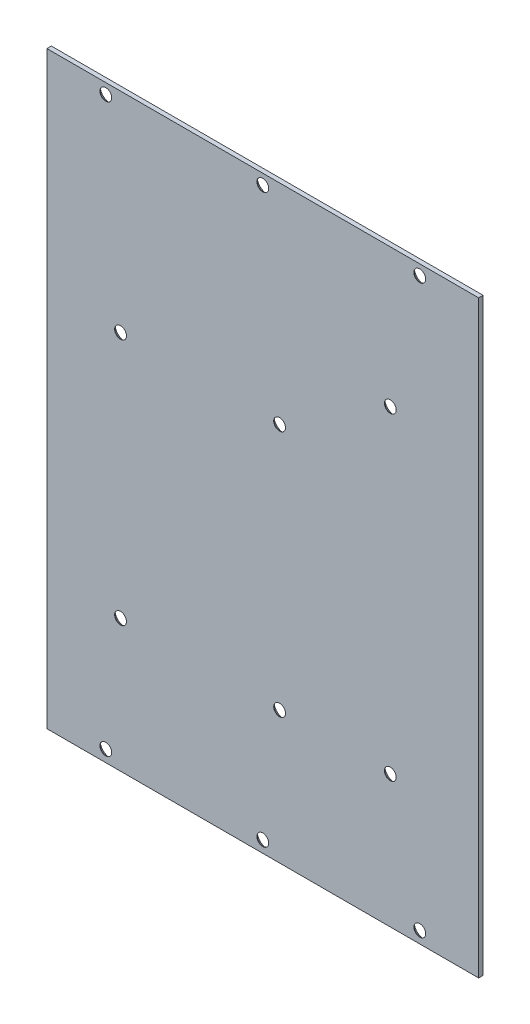
SolidWorks part; units mm, degrees
ref_plane "Спереди" through (0, 0, 0) normal (0, 0, 1) x (1, 0, 0)
ref_plane "Сверху" through (0, 0, 0) normal (0, 1, 0) x (1, 0, 0)
ref_plane "Справа" through (0, 0, 0) normal (1, 0, 0) x (0, 0, -1)
sketch "Эскиз1" plane through (0, 0, 0) normal (0, 0, 1) x (1, 0, 0)
  line L1 (0, 0) -> (146.6, 0)
  line L2 (0, 0) -> (0, 200)
  line L3 (0, 200) -> (146.6, 200)
  line L4 (146.6, 0) -> (146.6, 200)
  dimension "D1" = 146.6
  dimension "D2" = 200
extrude "Бобышка-Вытянуть1" add sketch "Эскиз1" along normal blind 1.5
sketch "Эскиз2" plane through (0, 0, 1.5) normal (0, 0, 1) x (1, 0, 0)
  line L0 (0, 0) -> (146.6, 0) construction
  line L1 (0, 200) -> (0, 0) construction
  line L2 (146.6, 200) -> (0, 200) construction
  circle A0 centre (20, 4) radius 2
  circle A1 centre (20, 196.5) radius 2
  circle A2 centre (73.3, 196.5) radius 2
  circle A3 centre (73.3, 4) radius 2
  circle A4 centre (126.6, 196.5) radius 2
  circle A5 centre (126.6, 4) radius 2
  dimension "D1" = 4
  dimension "D2" = 4
  dimension "D3" = 20
  dimension "D4" = 3.5
  dimension "D5" = 3
extrude "Вырез-Вытянуть1" cut sketch "Эскиз2" against normal through all
sketch "Эскиз3" plane through (0, 0, 1.5) normal (0, 0, 1) x (1, 0, 0)
  line L0 (0, 0) -> (146.6, 0) construction
  line L1 (0, 200) -> (0, 0) construction
  circle A0 centre (25, 45) radius 2
  circle A1 centre (79, 45) radius 2
  circle A2 centre (79, 129) radius 2
  circle A3 centre (25, 129) radius 2
  dimension "D1" = 4
  dimension "D2" = 45
  dimension "D3" = 25
extrude "Вырез-Вытянуть2" cut sketch "Эскиз3" against normal through all
sketch "Эскиз4" plane through (0, 0, 1.5) normal (0, 0, 1) x (1, 0, 0)
  line L0 (146.6, 0) -> (146.6, 200) construction
  line L1 (0, 0) -> (146.6, 0) construction
  circle A0 centre (116.6, 45) radius 2
  circle A1 centre (116.6, 153) radius 2
  dimension "D1" = 4
  dimension "D2" = 108
  dimension "D3" = 30
  dimension "D4" = 45
extrude "Вырез-Вытянуть3" cut sketch "Эскиз4" against normal through all
chamfer "Фаска1" distance 1.4 angle 45 12 edges at (128.6, 4, 0) (118.6, 45, 0) (81, 45, 0) (75.3, 4, 0) (22, 4, 0) (27, 45, 0) (27, 129, 0) (22, 196.5, 0) (75.3, 196.5, 0) (81, 129, 0) (118.6, 153, 0) (128.6, 196.5, 0)
